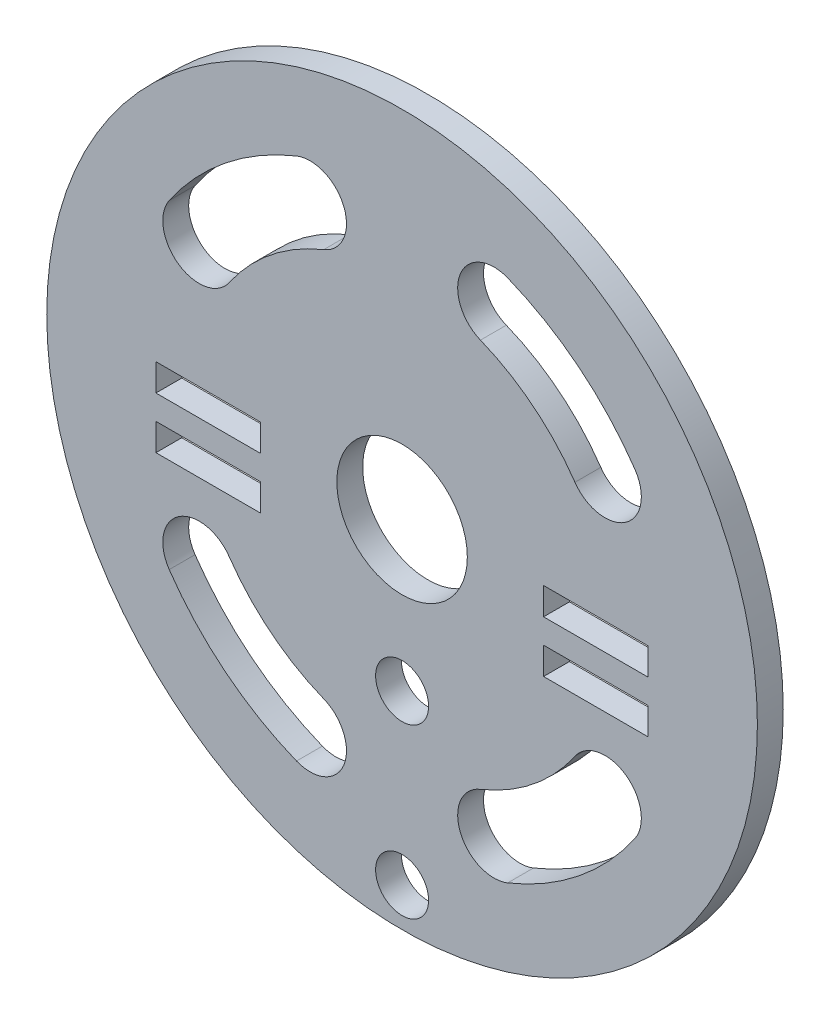
SolidWorks part; units mm, degrees
ref_plane "前视基准面" through (0, 0, 0) normal (0, 0, 1) x (1, 0, 0)
ref_plane "上视基准面" through (0, 0, 0) normal (0, 1, 0) x (1, 0, 0)
ref_plane "右视基准面" through (0, 0, 0) normal (1, 0, 0) x (0, 0, -1)
sketch "草图1" plane through (0, 0, 0) normal (0, 0, 1) x (1, 0, 0)
  line L0 (0, 0) -> (0, 4) construction
  line L1 (0, 4) -> (-15, 4) construction
  line L2 (0, 2) -> (-3.9018, 2) construction
  line L3 (-19.05, 5.05) -> (-10.95, 5.05)
  line L4 (-19.05, 5.05) -> (-19.05, 2.95)
  line L5 (-19.05, 2.95) -> (-10.95, 2.95)
  line L6 (-10.95, 5.05) -> (-10.95, 2.95)
  line L7 (-19.05, 5.05) -> (-10.95, 2.95) construction
  line L8 (-19.05, 2.95) -> (-10.95, 5.05) construction
  line L9 (-10.95, -1.05) -> (-10.95, 1.05)
  line L10 (-19.05, -1.05) -> (-10.95, -1.05)
  line L11 (-19.05, -1.05) -> (-19.05, 1.05)
  line L12 (-19.05, 1.05) -> (-10.95, 1.05)
  line L13 (10.95, 5.05) -> (10.95, 2.95)
  line L14 (19.05, 5.05) -> (10.95, 5.05)
  line L15 (19.05, 5.05) -> (19.05, 2.95)
  line L16 (19.05, 2.95) -> (10.95, 2.95)
  line L17 (19.05, 1.05) -> (10.95, 1.05)
  line L18 (19.05, -1.05) -> (19.05, 1.05)
  line L19 (19.05, -1.05) -> (10.95, -1.05)
  line L20 (10.95, -1.05) -> (10.95, 1.05)
  circle A0 centre (0, 0) radius 2.05 construction
  circle A1 centre (0, 4) radius 2.05 construction
  circle A2 centre (0, 4) radius 5.05
  circle A4 centre (0, 4) radius 12 construction
  circle A6 centre (0, 4) radius 27.5
  circle A7 centre (0, -7.5) radius 2.05
  circle A8 centre (0, 4) radius 24.5 construction
  circle A9 centre (0, -20.5) radius 2.05
  arc A10 (15.7016, 14.7772) -> (7.1176, 21.6643) centre (0, 4) ccw construction
  circle A15 centre (0, 4) radius 19.0444 construction
  arc A16 (-15.7016, -6.7772) -> (-7.1176, -13.6643) centre (0, 4) ccw construction
  arc A17 (-18.0227, -8.3704) -> (-8.1698, -16.2756) centre (0, 4) ccw
  arc A18 (-13.3805, -5.1841) -> (-6.0655, -11.0531) centre (0, 4) ccw
  arc A19 (-13.3805, -5.1841) -> (-18.0227, -8.3704) centre (-15.7016, -6.7772) ccw
  arc A20 (-8.1698, -16.2756) -> (-6.0655, -11.0531) centre (-7.1176, -13.6643) ccw
  arc A21 (15.7016, -6.7772) -> (7.1176, -13.6643) centre (0, 4) cw construction
  arc A22 (18.0227, -8.3704) -> (8.1698, -16.2756) centre (0, 4) cw
  arc A23 (13.3805, -5.1841) -> (6.0655, -11.0531) centre (0, 4) cw
  arc A24 (13.3805, -5.1841) -> (18.0227, -8.3704) centre (15.7016, -6.7772) cw
  arc A25 (8.1698, -16.2756) -> (6.0655, -11.0531) centre (7.1176, -13.6643) cw
  arc A26 (18.0227, 16.3704) -> (8.1698, 24.2756) centre (0, 4) ccw
  arc A27 (13.3805, 13.1841) -> (6.0655, 19.0531) centre (0, 4) ccw
  arc A28 (13.3805, 13.1841) -> (18.0227, 16.3704) centre (15.7016, 14.7772) ccw
  arc A29 (8.1698, 24.2756) -> (6.0655, 19.0531) centre (7.1176, 21.6643) ccw
  arc A30 (-15.7016, 14.7772) -> (-7.1176, 21.6643) centre (0, 4) cw construction
  arc A31 (-18.0227, 16.3704) -> (-8.1698, 24.2756) centre (0, 4) cw
  arc A32 (-13.3805, 13.1841) -> (-6.0655, 19.0531) centre (0, 4) cw
  arc A33 (-13.3805, 13.1841) -> (-18.0227, 16.3704) centre (-15.7016, 14.7772) cw
  arc A34 (-8.1698, 24.2756) -> (-6.0655, 19.0531) centre (-7.1176, 21.6643) cw
  point P35 (11.918, 18.8543)
  point P43 (-11.918, -10.8543)
  point P50 (11.918, -10.8543)
  point P57 (-11.918, 18.8543)
  dimension "D1" = 4.1
  dimension "D3" = 4.1
  dimension "D7" = 10.1
  dimension "D9" = 24
  dimension "D10" = 55
  dimension "D11" = 7.5
  dimension "D12" = 3
  dimension "D2" = 4
  dimension "D4" = 15
  dimension "D5" = 8.1
  dimension "D6" = 2.1
  dimension "D8" = 0
extrude "凸台-拉伸1" add sketch "草图1" along normal blind 2
